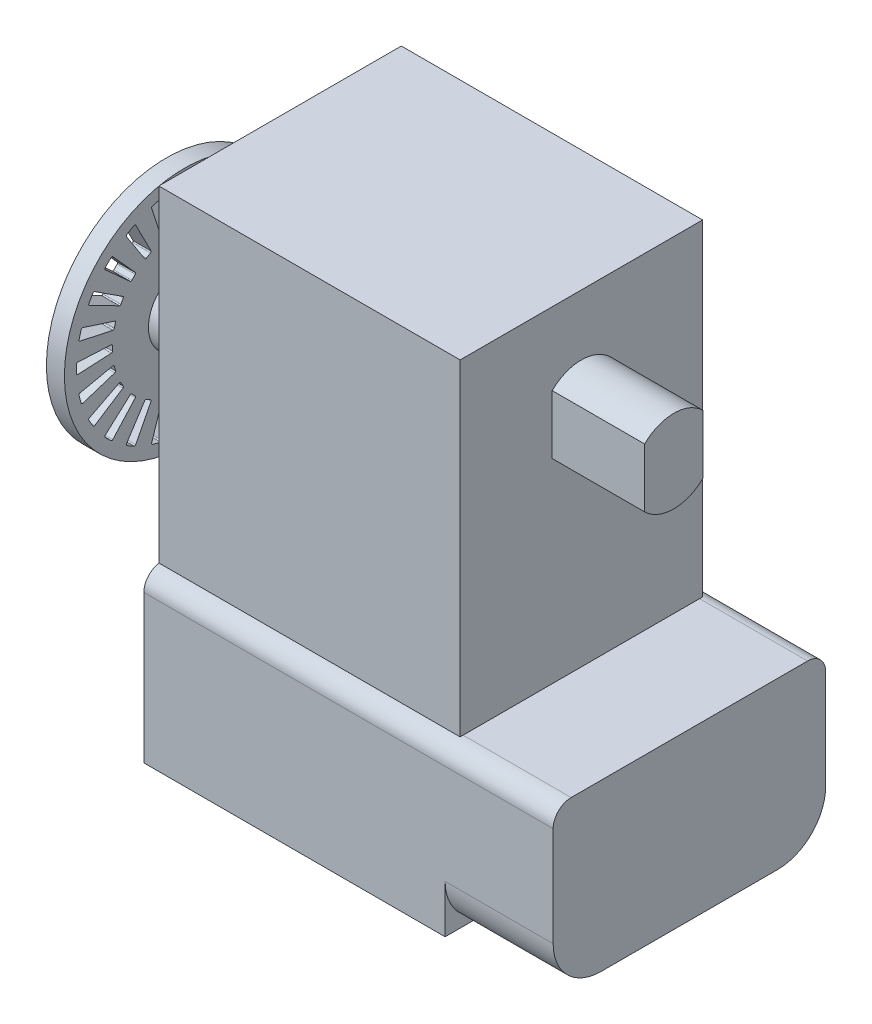
SolidWorks part; units mm, degrees
ref_plane "Plan de face" through (0, 0, 0) normal (0, 0, 1) x (1, 0, 0)
ref_plane "Plan de dessus" through (0, 0, 0) normal (0, 1, 0) x (1, 0, 0)
ref_plane "Plan de droite" through (0, 0, 0) normal (1, 0, 0) x (0, 0, -1)
sketch "Esquisse1" plane through (0, 0, 0) normal (0, 0, 1) x (1, 0, 0)
  line L1 (0, 0) -> (25.1, 0)
  line L2 (0, 0) -> (0, 27.2)
  line L3 (0, 27.2) -> (25.1, 27.2)
  line L4 (25.1, 0) -> (25.1, 27.2)
  dimension "D1" = 27.2
  dimension "D2" = 25.1
extrude "Extrusion1" add sketch "Esquisse1" along normal blind 20.2
sketch "Esquisse2" plane through (0, 0, 0) normal (-1, 0, 0) x (0, 0, 1)
  line L0 (20.2, 27.2) -> (0, 27.2) construction
  line L1 (0.25, 0) -> (19.95, 0)
  line L2 (-1.25, -1.5) -> (-1.25, -13.8)
  line L3 (-1.25, -13.8) -> (21.45, -13.8)
  line L4 (21.45, -1.5) -> (21.45, -13.8)
  line L5 (20.2, 0) -> (0, 0) construction
  line L6 (10.1, 27.2) -> (10.1, -17.3851) construction
  arc A0 (0.25, 0) -> (-1.25, -1.5) centre (0.25, -1.5) ccw
  arc A1 (19.95, 0) -> (21.45, -1.5) centre (19.95, -1.5) cw
  dimension "D3" = 1.5
  dimension "D4" = 1.5
  dimension "D1" = 41
  dimension "D2" = 22.7
extrude "Extrusion2" add sketch "Esquisse2" against normal up to surface (25.1 mm away) up to face at (25.1, 13.6, 10.1)
sketch "Esquisse4" plane through (25.1, 0, 0) normal (1, 0, 0) x (0, 0, -1)
  line L0 (1.25, -13.8) -> (1.25, -1.5) construction
  line L1 (-21.45, -1.5) -> (-21.45, -13.8) construction
  line L2 (1.25, -9.8) -> (1.25, -1.5)
  line L3 (-21.45, -1.5) -> (-21.45, -9.8)
  line L4 (-19.95, 0) -> (-0.25, 0)
  line L5 (-17.45, -13.8) -> (-2.75, -13.8)
  arc A0 (1.25, -1.5) -> (-0.25, 0) centre (-0.25, -1.5) ccw construction
  arc A1 (-19.95, 0) -> (-21.45, -1.5) centre (-19.95, -1.5) ccw construction
  arc A2 (1.25, -1.5) -> (-0.25, 0) centre (-0.25, -1.5) ccw
  arc A3 (-19.95, 0) -> (-21.45, -1.5) centre (-19.95, -1.5) ccw
  arc A4 (-21.45, -9.8) -> (-17.45, -13.8) centre (-17.45, -9.8) ccw
  arc A5 (1.25, -9.8) -> (-2.75, -13.8) centre (-2.75, -9.8) cw
  dimension "D1" = 4
extrude "Extrusion3" add sketch "Esquisse4" along normal blind 9
sketch "Esquisse5" plane through (25.1, 0, 0) normal (1, 0, 0) x (0, 0, -1)
  line L0 (-20.2, 27.2) -> (0, 27.2) construction
  line L1 (-20.2, 0) -> (-20.2, 27.2) construction
  line L4 (-12.529, 21.15) -> (-12.529, 16.25)
  line L6 (-7.671, 21.15) -> (-7.671, 16.25)
  arc A0 (-12.529, 16.25) -> (-7.671, 16.25) centre (-10.1, 18.7) ccw
  arc A1 (-7.671, 21.15) -> (-12.529, 21.15) centre (-10.1, 18.7) ccw
  dimension "D3" = 6.9
  dimension "D1" = 8.5
  dimension "D2" = 10.1
  dimension "D4" = 4.9
extrude "Extrusion4" add sketch "Esquisse5" along normal blind 7.7
sketch "Esquisse6" plane through (0, 0, 0) normal (-1, 0, 0) x (0, 0, 1)
  line L0 (20.2, 27.2) -> (0, 27.2) construction
  line L1 (20.2, 27.2) -> (20.2, 0) construction
  circle A0 centre (10.1, 9.45) radius 1.25
  dimension "D3" = 2.5
  dimension "D1" = 17.75
  dimension "D2" = 10.1
extrude "Extrusion5" add sketch "Esquisse6" along normal blind 10
ref_axis "Axe1" through (0, 9.45, 10.1) along (-1, 0, 0)
ref_plane "Plan2" through (0, 0, 10.1) normal (0, 0, 1) x (1, 0, 0)
sketch "Esquisse7" plane through (0, 0, 10.1) normal (0, 0, 1) x (1, 0, 0)
  line L0 (-9.47, 10.7) -> (-9.47, 19.45)
  line L1 (-9.47, 19.45) -> (-7.97, 19.45)
  line L2 (-7.97, 19.45) -> (-7.97, 12.45)
  line L3 (-7.97, 12.45) -> (-3.47, 12.45)
  line L4 (-3.47, 12.45) -> (-3.47, 10.7)
  line L5 (-3.47, 10.7) -> (-9.47, 10.7)
  line L6 (0, 10.7) -> (-10, 10.7) construction
  line L7 (-10, 10.7) -> (-10, 8.2) construction
  line L8 (0, 9.45) -> (-10, 9.45) construction
  dimension "D1" = 0.53
  dimension "D2" = 1.5
  dimension "D3" = 6
  dimension "D4" = 3
  dimension "D5" = 10
revolve "Révolution1" add sketch "Esquisse7" angle 360 about axis through (0, 9.45, 10.1) along (-1, 0, 0)
sketch "Esquisse8" plane through (-9.47, 0, 0) normal (-1, 0, 0) x (0, 0, 1)
  line L0 (10.1, -22.55) -> (10.1, 22.55) construction
  line L1 (9.797, 15.5415) -> (9.6551, 18.3382)
  line L2 (10.403, 15.5415) -> (10.5449, 18.3382)
  line L3 (10.1, 9.45) -> (10.1, 20.9541) construction
  arc A0 (10.4489, 18.4432) -> (9.7511, 18.4432) centre (10.1, 9.45) ccw
  arc A1 (10.2998, 15.4467) -> (9.9002, 15.4467) centre (10.1, 9.45) ccw
  circle A2 centre (10.1, 9.45) radius 1.25 construction
  circle A3 centre (10.1, 9.45) radius 10 construction
  arc A4 (9.6551, 18.3382) -> (9.7511, 18.4432) centre (9.755, 18.3433) cw
  arc A5 (10.5449, 18.3382) -> (10.4489, 18.4432) centre (10.445, 18.3433) ccw
  arc A6 (10.403, 15.5415) -> (10.2998, 15.4467) centre (10.3031, 15.5466) cw
  arc A7 (9.797, 15.5415) -> (9.9002, 15.4467) centre (9.8969, 15.5466) ccw
  point P14 (9.65, 18.4387)
  point P17 (10.55, 18.4387)
  dimension "D2" = 3
  dimension "D3" = 1
  dimension "D4" = 0.1
  dimension "D1" = 0.9
extrude "Enlèv. mat.-Extru.1" cut sketch "Esquisse8" against normal up to next
pattern_circular "Répétition circulaire1" count 24 over 360 about axis through (0, 9.45, 10.1) along (1, 0, 0) of "Enlèv. mat.-Extru.1"
